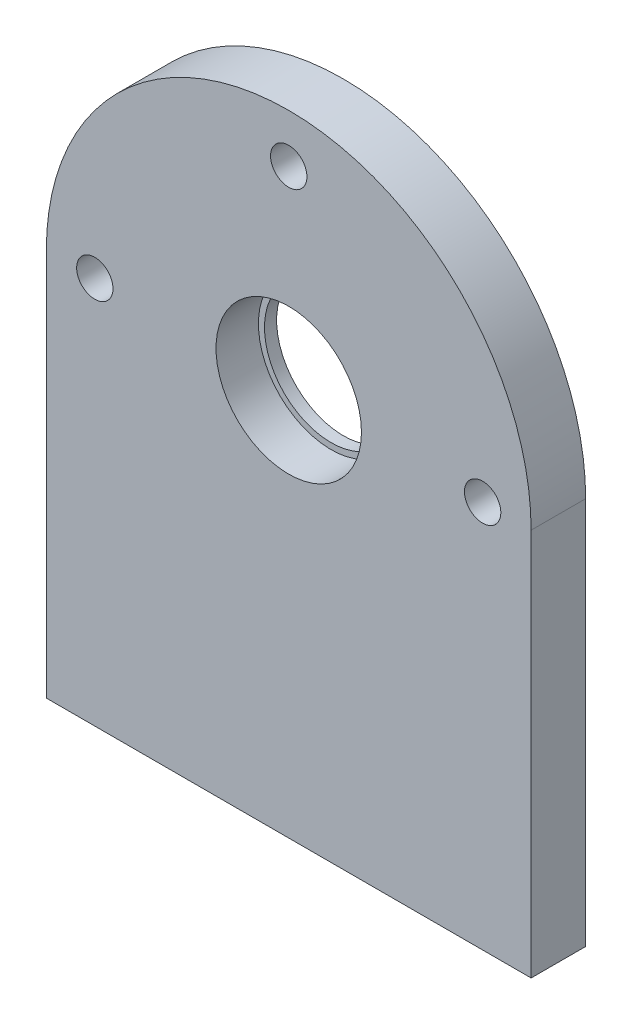
SolidWorks part; units mm, degrees
ref_plane "前视基准面" through (0, 0, 0) normal (0, 0, 1) x (1, 0, 0)
ref_plane "上视基准面" through (0, 0, 0) normal (0, 1, 0) x (1, 0, 0)
ref_plane "右视基准面" through (0, 0, 0) normal (1, 0, 0) x (0, 0, -1)
sketch "草图1" plane through (0, 0, 0) normal (0, 0, 1) x (1, 0, 0)
  line L0 (-20, 0) -> (-20, -32)
  line L4 (20, 0) -> (20, -32)
  line L5 (20, -32) -> (-20, -32)
  circle A4 centre (0, 0) radius 6
  arc A5 (20, 0) -> (-20, 0) centre (0, 0) ccw
  dimension "D1" = 40
  dimension "D2" = 12
  dimension "D3" = 32
extrude "凸台-拉伸1" add sketch "草图1" along normal blind 4.5
sketch "草图3" plane through (0, 0, 0) normal (0, 0, 1) x (1, 0, 0)
  circle A0 centre (0, 0) radius 6
  circle A1 centre (0, 0) radius 5.5
  dimension "D1" = 12
  dimension "D2" = 11
extrude "凸台-拉伸2" add sketch "草图3" along normal blind 1
sketch "草图5" plane through (0, 0, 0) normal (0, 0, 1) x (1, 0, 0)
  line L0 (-16, 0) -> (16, 0) construction
  line L1 (0, 16) -> (0, -16) construction
  circle A0 centre (0, 0) radius 16 construction
  circle A1 centre (0, 16) radius 1.5
  circle A2 centre (-16, 0) radius 1.5
  circle A3 centre (16, 0) radius 1.5
  dimension "D1" = 32
extrude "切除-拉伸3" cut sketch "草图5" along normal through all both and the other way through all
sketch "草图6" plane through (0, -32, 0) normal (0, -1, 0) x (1, 0, 0)
  line L0 (-20, 4.5) -> (20, 4.5) construction
  circle A0 centre (9, 2.25) radius 1.5
  circle A1 centre (-9, 2.25) radius 1.5
  dimension "D1" = 3
  dimension "D2" = 3
  dimension "D5" = 2.25
  dimension "D6" = 2.25
  dimension "D3" = 9
  dimension "D4" = 9
extrude "切除-拉伸4" cut sketch "草图6" against normal blind 5
